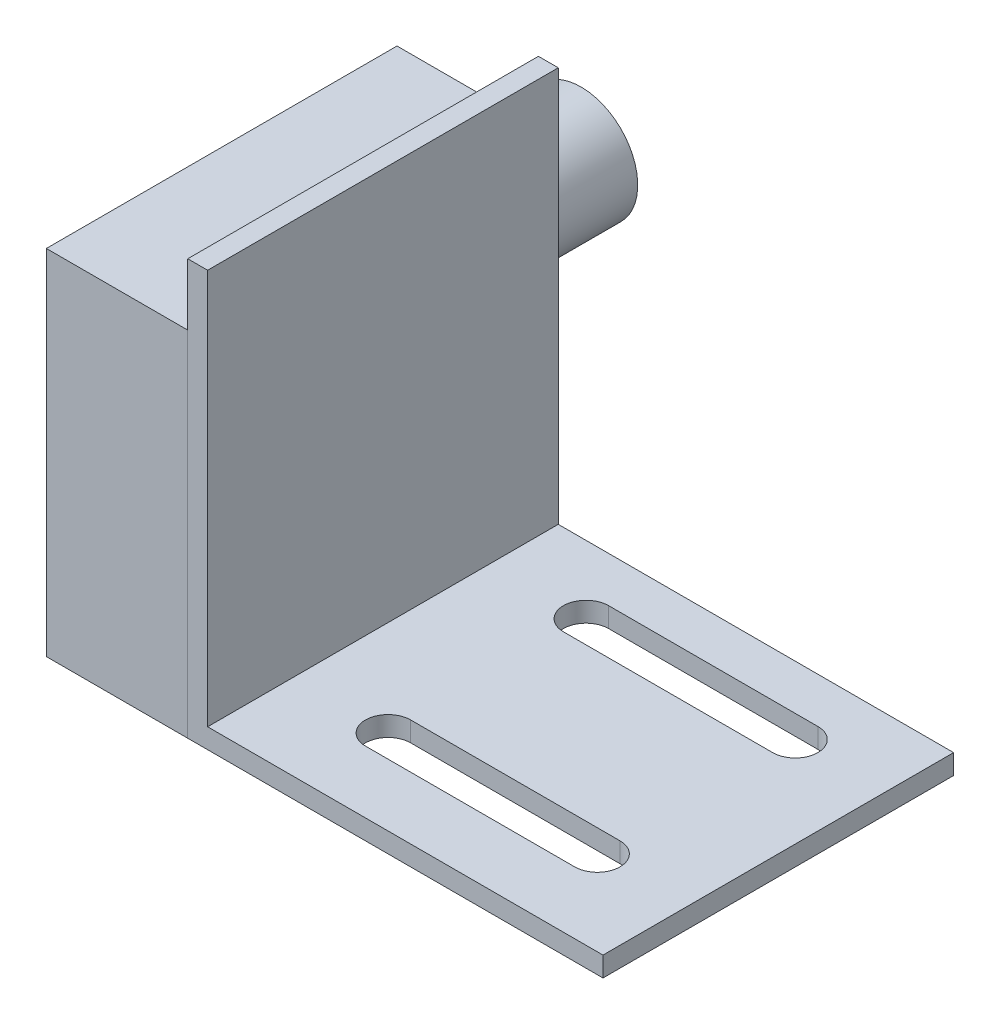
SolidWorks part; units mm, degrees
ref_plane "Front Plane" through (0, 0, 0) normal (0, 0, 1) x (1, 0, 0)
ref_plane "Top Plane" through (0, 0, 0) normal (0, 1, 0) x (1, 0, 0)
ref_plane "Right Plane" through (0, 0, 0) normal (1, 0, 0) x (0, 0, -1)
sketch "Sketch1" plane through (0, 0, 0) normal (0, 0, 1) x (1, 0, 0)
  line L9 (0, 0) -> (0, 37.2983)
  line L10 (0, 37.2983) -> (1.7849, 37.2983)
  line L11 (1.7849, 37.2983) -> (1.7849, 1.7849)
  line L12 (1.7849, 1.7849) -> (37.2983, 1.7849)
  line L13 (37.2983, 1.7849) -> (37.2983, 0)
  line L14 (37.2983, 0) -> (0, 0)
  dimension "D1" = 1.7849
  dimension "D2" = 1.7849
  dimension "D3" = 37.2983
  dimension "D4" = 37.2983
extrude "Boss-Extrude1" add sketch "Sketch1" along normal mid plane 31.496
sketch "Sketch2" plane through (0, 0, 0) normal (-1, 0, 0) x (0, 0, 1)
  line L0 (-15.748, 37.2983) -> (-15.748, 0) construction
  line L1 (15.748, 0) -> (-15.748, 0)
  line L2 (15.748, 0) -> (15.748, 31.75)
  line L3 (15.748, 31.75) -> (-15.748, 31.75)
  line L4 (-15.748, 0) -> (-15.748, 31.75)
  dimension "D1" = 31.75
extrude "Boss-Extrude2" add sketch "Sketch2" along normal blind 12.7 separate body
sketch "Sketch4" plane through (0, 0, -15.748) normal (0, 0, -1) x (-1, 0, 0)
  line L0 (12.7, 31.75) -> (12.7, 0) construction
  line L1 (12.7, 31.75) -> (0, 31.75) construction
  circle A0 centre (6.3209, 21.59) radius 5.08
  dimension "D3" = 10.16
  dimension "D1" = 6.3791
  dimension "D2" = 10.16
extrude "Boss-Extrude3" add sketch "Sketch4" along normal blind 10.16
sketch "Sketch6" plane through (0, 1.7849, 0) normal (0, 1, 0) x (1, 0, 0)
  line L0 (29.1703, 11.684) -> (10.3743, 11.684)
  line L1 (29.1703, 7.62) -> (10.3743, 7.62)
  line L3 (0, 15.748) -> (37.2983, 15.748) construction
  line L5 (37.2983, -15.748) -> (37.2983, 15.748) construction
  arc A0 (29.1703, 7.62) -> (29.1703, 11.684) centre (29.1703, 9.652) ccw
  arc A2 (10.3743, 11.684) -> (10.3743, 7.62) centre (10.3743, 9.652) ccw
  dimension "D1" = 4.064
  dimension "D2" = 4.064
  dimension "D4" = 18.796
  dimension "D7" = 8.128
extrude "Cut-Extrude1" cut sketch "Sketch6" against normal through all
pattern_linear "LPattern1" count 2 spacing 17.78 along (0, 0, 1) of "Cut-Extrude1"
equation "\"D2@Sketch1\"=\"D1@Sketch1\""
equation "\"D4@Sketch1\"=\"D3@Sketch1\""
